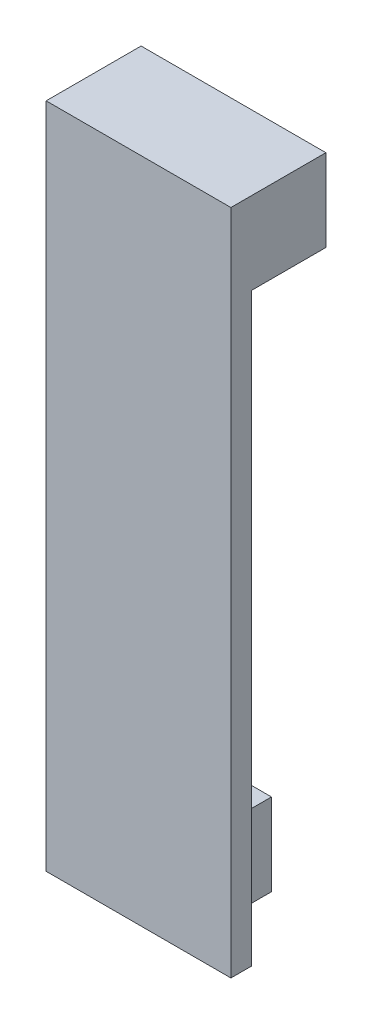
SolidWorks part; units mm, degrees
ref_plane "Front Plane" through (0, 0, 0) normal (0, 0, 1) x (1, 0, 0)
ref_plane "Top Plane" through (0, 0, 0) normal (0, 1, 0) x (1, 0, 0)
ref_plane "Right Plane" through (0, 0, 0) normal (1, 0, 0) x (0, 0, -1)
sketch "Basic Shape Sketch" plane through (0, 0, 0) normal (0, 0, 1) x (1, 0, 0)
  line L5 (-9, -32.5) -> (9, -32.5)
  line L6 (-9, -32.5) -> (-9, 32.5)
  line L7 (-9, 32.5) -> (9, 32.5)
  line L8 (9, -32.5) -> (9, 32.5)
  line L9 (-9, -32.5) -> (9, 32.5) construction
  line L10 (-9, 32.5) -> (9, -32.5) construction
  point P0 (0, 0)
  dimension "D1" = 65
  dimension "D2" = 18
extrude "Basic Shape" add sketch "Basic Shape Sketch" along normal blind 2
sketch "Connector Sketch" plane through (0, 0, 0) normal (0, 0, -1) x (-1, 0, 0)
  line L1 (-3.7, -32.5) -> (3.7, -32.5)
  line L2 (-3.7, -32.5) -> (-3.7, -24.5)
  line L3 (-3.7, -24.5) -> (3.7, -24.5)
  line L4 (3.7, -32.5) -> (3.7, -24.5)
  line L5 (9, -32.5) -> (-9, -32.5) construction
  point P6 (0, -32.5)
  point P7 (0, -32.5)
  dimension "D1" = 8
  dimension "D2" = 7.4
extrude "Connector" add sketch "Connector Sketch" along normal blind 7.25
sketch "Connector Holes Sketch" plane through (0, -32.5, 0) normal (0, -1, 0) x (1, 0, 0)
  line L0 (0, 2) -> (0, -7.25) construction
  line L1 (-3.2, -1.25) -> (-0.2, -1.25)
  line L2 (-3.2, -1.25) -> (-3.2, -5.75)
  line L3 (-3.2, -5.75) -> (-0.2, -5.75)
  line L4 (-0.2, -1.25) -> (-0.2, -5.75)
  line L5 (0.2, -1.25) -> (3.2, -1.25)
  line L6 (0.2, -1.25) -> (0.2, -5.75)
  line L7 (0.2, -5.75) -> (3.2, -5.75)
  line L8 (3.2, -1.25) -> (3.2, -5.75)
  line L9 (3.7, -7.25) -> (-3.7, -7.25) construction
  line L10 (-9, 2) -> (9, 2) construction
  line L11 (-0.2, -3.5) -> (0.2, -3.5) construction
  point P13 (0, -7.25)
  point P17 (0, 2)
  point P20 (-0.2, -3.5)
  point P25 (0.2, -3.5)
  point P26 (0, -3.5)
  dimension "D1" = 0.4
  dimension "D2" = 4.5
  dimension "D3" = 3
  dimension "D4" = 1.5
extrude "Connector Holes" cut sketch "Connector Holes Sketch" against normal blind 5
sketch "Sketch1" plane through (0, 0, 0) normal (0, 0, -1) x (-1, 0, 0)
  line L0 (-9, 32.5) -> (9, 32.5) construction
  line L1 (-9, 32.5) -> (9, 32.5)
  line L2 (-9, 32.5) -> (-9, 24.5)
  line L3 (-9, 24.5) -> (9, 24.5)
  line L4 (9, 32.5) -> (9, 24.5)
  point P6 (0, 32.5)
  point P7 (0, 32.5)
  dimension "D1" = 18
  dimension "D2" = 8
extrude "Boss-Extrude1" add sketch "Sketch1" along normal blind 7.25
